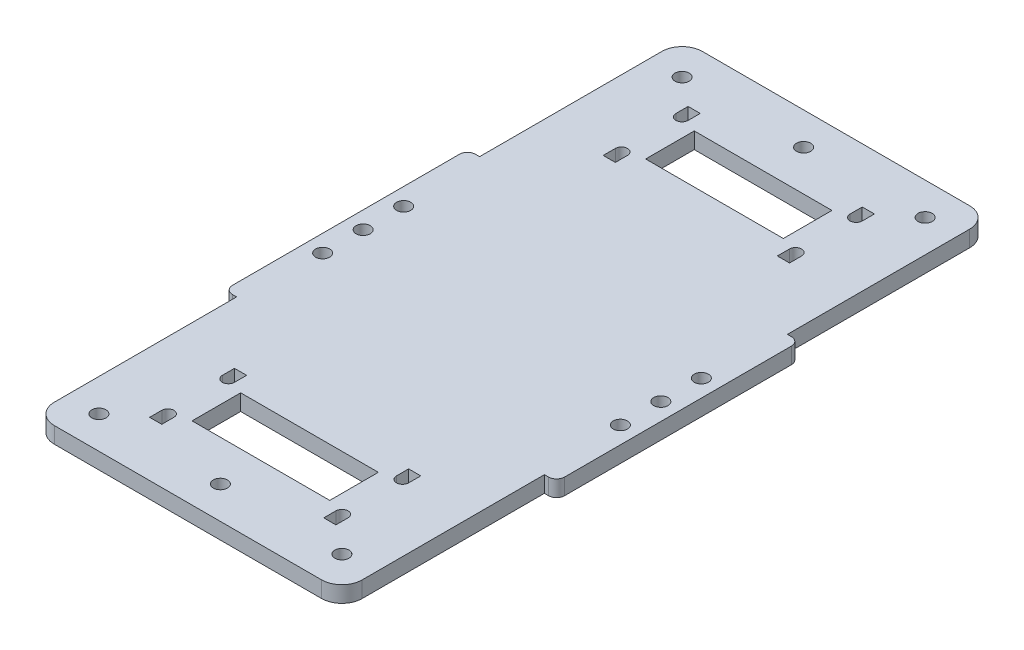
SolidWorks part; units mm, degrees
ref_plane "前视基准面" through (0, 0, 0) normal (0, 0, 1) x (1, 0, 0)
ref_plane "上视基准面" through (0, 0, 0) normal (0, 1, 0) x (1, 0, 0)
ref_plane "右视基准面" through (0, 0, 0) normal (1, 0, 0) x (0, 0, -1)
sketch "草图1" plane through (0, 0, 0) normal (0, 1, 0) x (1, 0, 0)
  line L1 (-41, 50) -> (41, 50)
  line L2 (-41, 50) -> (-41, -50)
  line L3 (-41, -50) -> (41, -50)
  line L4 (41, 50) -> (41, -50)
  line L5 (-41, 50) -> (41, -50) construction
  line L6 (-41, -50) -> (41, 50) construction
  point P0 (0, 0)
  dimension "D1" = 100
  dimension "D2" = 82
extrude "凸台-拉伸1" add sketch "草图1" along normal blind 4
sketch "草图2" plane through (0, 0, 50) normal (0, 0, 1) x (1, 0, 0)
  line L4 (-41, 0) -> (41, 0)
  line L5 (41, 0) -> (41, 4)
  line L6 (41, 4) -> (-41, 4)
  line L7 (-41, 4) -> (-41, 0)
  line L8 (-41, 0) -> (41, 0)
  line L9 (41, 0) -> (41, 4)
  line L10 (41, 4) -> (-41, 4)
  line L11 (-41, 4) -> (-41, 0)
  dimension "D1" = 0
extrude "凸台-拉伸2" add sketch "草图2" along normal blind 60
sketch "草图3" plane through (0, 4, 0) normal (0, 1, 0) x (1, 0, 0)
  line L1 (-41, 50) -> (-38, 50)
  line L2 (-41, 50) -> (-41, 0)
  line L3 (-41, 0) -> (-38, 0)
  line L4 (-38, 50) -> (-38, 0)
  line L5 (41, 50) -> (38, 50)
  line L6 (41, 50) -> (41, 0)
  line L7 (41, 0) -> (38, 0)
  line L8 (38, 50) -> (38, 0)
  line L9 (-41, -110) -> (-38, -110)
  line L10 (-41, -110) -> (-41, -60)
  line L11 (-41, -60) -> (-38, -60)
  line L12 (-38, -110) -> (-38, -60)
  line L13 (41, -110) -> (38, -110)
  line L14 (41, -110) -> (41, -60)
  line L15 (41, -60) -> (38, -60)
  line L16 (38, -110) -> (38, -60)
  dimension "D1" = 50
  dimension "D2" = 3
  dimension "D3" = 3
  dimension "D4" = 50
  dimension "D5" = 3
  dimension "D6" = 3
  dimension "D7" = 50
extrude "切除-拉伸1" cut sketch "草图3" against normal through all both and the other way through all
sketch "草图5" plane through (0, 4, 0) normal (0, 1, 0) x (1, 0, 0)
  line L0 (38, 50) -> (-38, 50) construction
  line L1 (-38, 0) -> (-38, 50) construction
  circle A0 centre (-30, 42) radius 1.75
  dimension "D1" = 3.5
  dimension "D2" = 8
  dimension "D3" = 8
extrude "切除-拉伸2" cut sketch "草图5" against normal through all both and the other way through all
sketch "草图6" plane through (0, 4, 0) normal (0, 1, 0) x (1, 0, 0)
  line L0 (38, 50) -> (-38, 50) construction
  line L1 (38, 50) -> (38, 0) construction
  line L2 (-38, -110) -> (-38, -60) construction
  line L3 (38, -110) -> (-38, -110) construction
  line L4 (38, -60) -> (38, -110) construction
  circle A0 centre (30, 42) radius 1.75
  circle A1 centre (-30, -102) radius 1.75
  circle A2 centre (30, -102) radius 1.75
  dimension "D1" = 3.5
  dimension "D4" = 8
  dimension "D5" = 8
  dimension "D6" = 8
  dimension "D7" = 3.5
  dimension "D8" = 3.5
  dimension "D9" = 8
  dimension "D2" = 8
  dimension "D3" = 8
extrude "切除-拉伸3" cut sketch "草图6" against normal through all both and the other way through all
sketch "草图7" plane through (0, 4, 0) normal (0, 1, 0) x (1, 0, 0)
  line L1 (-17, -92) -> (17, -92)
  line L2 (-17, -92) -> (-17, -80)
  line L3 (-17, -80) -> (17, -80)
  line L4 (17, -92) -> (17, -80)
  line L5 (-17, 20) -> (17, 20)
  line L6 (-17, 20) -> (-17, 32)
  line L7 (-17, 32) -> (17, 32)
  line L8 (17, 20) -> (17, 32)
extrude "切除-拉伸4" cut sketch "草图7" against normal through all both and the other way through all
fillet "圆角1" radius 5 4 edges at (-38, 2, 110) (38, 2, 110) (38, 2, -50) (-38, 2, -50)
fillet "圆角2" radius 2 4 edges at (41, 2, 60) (41, 2, 0) (-41, 2, 60) (-41, 2, 0)
sketch "草图8" plane through (0, 4, 0) normal (0, 1, 0) x (1, 0, 0)
  line L0 (0, 50) -> (0, -110) construction
  line L1 (33, 50) -> (-33, 50) construction
  line L2 (33, -110) -> (-33, -110) construction
  circle A0 centre (0, 42) radius 1.75
  circle A1 centre (0, -102) radius 1.75
  dimension "D1" = 3.5
  dimension "D3" = 3.5
  dimension "D4" = 8
  dimension "D2" = 8
extrude "切除-拉伸5" cut sketch "草图8" against normal through all both and the other way through all
sketch "草图9" plane through (0, 4, 0) normal (0, 1, 0) x (1, 0, 0)
  line L0 (17, 31.9775) -> (17, 33.4775) construction
  line L2 (17, 20) -> (17, 31.9775) construction
  line L3 (17, 31.9775) -> (26, 31.9775) construction
  line L5 (17, 33.4775) -> (17, 38.4775) construction
  line L6 (17, 33.4775) -> (26, 33.4775) construction
  line L7 (17, 33.4775) -> (17, 18.4775) construction
  line L8 (17, 18.4775) -> (25, 18.4775) construction
  line L9 (25, 20) -> (25, 18.4775) construction
  line L10 (20, 33.4775) -> (20, 36.4775)
  line L11 (17, 38.4775) -> (26, 38.4775) construction
  line L12 (17, 38.4775) -> (17, 31.9775) construction
  line L13 (17, 31.9775) -> (26, 31.9775) construction
  line L14 (26, 38.4775) -> (26, 31.9775) construction
  line L15 (20, 36.4775) -> (23, 36.4775)
  line L16 (23, 36.4775) -> (23, 33.4775)
  line L17 (0, 42) -> (0, 25.9975) construction
  line L18 (-23, 36.4775) -> (-23, 33.4775)
  line L19 (-20, 36.4775) -> (-23, 36.4775)
  line L20 (-20, 33.4775) -> (-20, 36.4775)
  line L21 (-41, -30) -> (41, -30) construction
  line L22 (-41, -2) -> (-41, -58) construction
  line L23 (41, -58) -> (41, -2) construction
  line L24 (26, -98.4775) -> (26, -91.9775) construction
  line L25 (17, -91.9775) -> (26, -91.9775) construction
  line L26 (17, -98.4775) -> (17, -91.9775) construction
  line L27 (17, -98.4775) -> (26, -98.4775) construction
  line L28 (17, -93.4775) -> (26, -93.4775) construction
  line L29 (17, -93.4775) -> (17, -98.4775) construction
  line L30 (17, -91.9775) -> (26, -91.9775) construction
  line L31 (17, -91.9775) -> (17, -93.4775) construction
  line L32 (-20, -93.4775) -> (-20, -96.4775)
  line L33 (-20, -96.4775) -> (-23, -96.4775)
  line L34 (-23, -96.4775) -> (-23, -93.4775)
  line L35 (23, -96.4775) -> (23, -93.4775)
  line L36 (20, -96.4775) -> (23, -96.4775)
  line L37 (20, -93.4775) -> (20, -96.4775)
  line L38 (0, 25.9975) -> (18, 25.9975) construction
  line L39 (26, 13.5174) -> (26, 20.0174) construction
  line L40 (17, 20.0174) -> (26, 20.0174) construction
  line L41 (17, 13.5174) -> (17, 20.0174) construction
  line L42 (17, 13.5174) -> (26, 13.5174) construction
  line L43 (17, 18.5174) -> (26, 18.5174) construction
  line L44 (17, 18.5174) -> (17, 13.5174) construction
  line L45 (17, 20.0174) -> (26, 20.0174) construction
  line L46 (17, 20.0174) -> (17, 18.5174) construction
  line L47 (-20, 18.5174) -> (-20, 15.5174)
  line L48 (-20, 15.5174) -> (-23, 15.5174)
  line L49 (-23, 15.5174) -> (-23, 18.5174)
  line L50 (23, 15.5174) -> (23, 18.5174)
  line L51 (20, 15.5174) -> (23, 15.5174)
  line L52 (20, 18.5174) -> (20, 15.5174)
  line L53 (17, -86) -> (30.5234, -86) construction
  line L54 (17, -92) -> (17, -80) construction
  line L55 (17, -80.0225) -> (17, -78.5225) construction
  line L56 (17, -80.0225) -> (26, -80.0225) construction
  line L57 (17, -78.5225) -> (17, -73.5225) construction
  line L58 (17, -78.5225) -> (26, -78.5225) construction
  line L59 (17, -73.5225) -> (26, -73.5225) construction
  line L60 (17, -73.5225) -> (17, -80.0225) construction
  line L61 (17, -80.0225) -> (26, -80.0225) construction
  line L62 (26, -73.5225) -> (26, -80.0225) construction
  line L63 (20, -78.5225) -> (20, -75.5225)
  line L64 (20, -75.5225) -> (23, -75.5225)
  line L65 (23, -75.5225) -> (23, -78.5225)
  line L66 (-23, -75.5225) -> (-23, -78.5225)
  line L67 (-20, -75.5225) -> (-23, -75.5225)
  line L68 (-20, -78.5225) -> (-20, -75.5225)
  arc A0 (20, 33.4775) -> (23, 33.4775) centre (21.5, 33.4775) ccw
  arc A1 (-20, 33.4775) -> (-23, 33.4775) centre (-21.5, 33.4775) cw
  arc A2 (-20, -93.4775) -> (-23, -93.4775) centre (-21.5, -93.4775) ccw
  arc A3 (20, -93.4775) -> (23, -93.4775) centre (21.5, -93.4775) cw
  arc A4 (-20, 18.5174) -> (-23, 18.5174) centre (-21.5, 18.5174) ccw
  arc A5 (20, 18.5174) -> (23, 18.5174) centre (21.5, 18.5174) cw
  arc A6 (20, -78.5225) -> (23, -78.5225) centre (21.5, -78.5225) ccw
  arc A7 (-20, -78.5225) -> (-23, -78.5225) centre (-21.5, -78.5225) cw
  dimension "D1" = 3
  dimension "D2" = 1.5
  dimension "D3" = 3
  dimension "D4" = 5
  dimension "D5" = 9
extrude "切除-拉伸6" cut sketch "草图9" against normal through all both and the other way through all
sketch "草图10" plane through (0, 4, 0) normal (0, 1, 0) x (1, 0, 0)
  line L0 (-38, 0) -> (-32.5, 0) construction
  line L1 (-32.5, 0) -> (-32.5, -60) construction
  line L2 (-41, -2) -> (-41, -58) construction
  line L3 (-32.5, 0) -> (-41, -60) construction
  line L4 (-32.5, 0) -> (-41, 0) construction
  line L5 (-32.5, 0) -> (-32.5, -60) construction
  line L6 (-32.5, -60) -> (-41, -60) construction
  line L7 (-41, 0) -> (-41, -60) construction
  line L8 (0, 0) -> (0, -55.2099) construction
  line L9 (-36.75, -30) -> (36.75, -30) construction
  line L10 (-38, -20) -> (42.9366, -20) construction
  line L11 (-36.75, -30) -> (-36.75, 7.5413) construction
  line L12 (36.75, -30) -> (36.75, 1.6956) construction
  circle A0 centre (-36.75, -30) radius 1.75
  circle A1 centre (36.75, -30) radius 1.75
  circle A2 centre (-36.75, -20) radius 1.75
  circle A3 centre (36.75, -20) radius 1.75
  circle A4 centre (-36.75, -40) radius 1.75
  circle A5 centre (36.75, -40) radius 1.75
  dimension "D4" = 3.5
  dimension "D1" = 8.5
  dimension "D2" = 60
  dimension "D3" = 8.5
  dimension "D5" = 10
extrude "切除-拉伸7" cut sketch "草图10" against normal through all both and the other way through all
